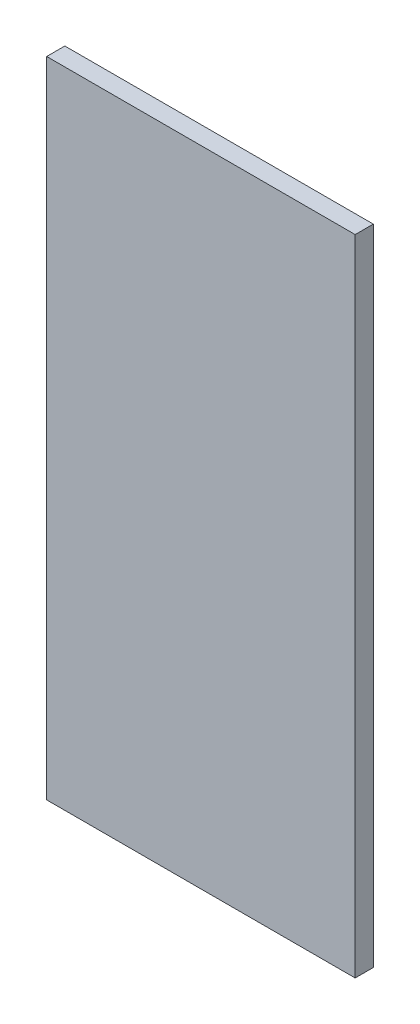
SolidWorks part; units mm, degrees
ref_plane "Front Plane" through (0, 0, 0) normal (0, 0, 1) x (1, 0, 0)
ref_plane "Top Plane" through (0, 0, 0) normal (0, 1, 0) x (1, 0, 0)
ref_plane "Right Plane" through (0, 0, 0) normal (1, 0, 0) x (0, 0, -1)
sketch "Sketch1" plane through (0, 0, 0) normal (0, 0, 1) x (1, 0, 0)
  line L1 (0, 0) -> (51, 0)
  line L2 (0, 0) -> (0, 106.45)
  line L3 (0, 106.45) -> (51, 106.45)
  line L4 (51, 0) -> (51, 106.45)
  dimension "D1" = 106.45
  dimension "D2" = 51
extrude "Boss-Extrude1" add sketch "Sketch1" along normal blind 3
